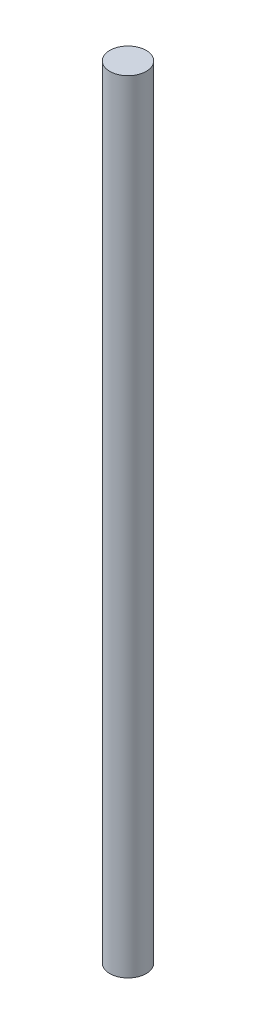
SolidWorks part; units mm, degrees
ref_plane "Płaszczyzna przednia" through (0, 0, 0) normal (0, 0, 1) x (1, 0, 0)
ref_plane "Płaszczyzna górna" through (0, 0, 0) normal (0, 1, 0) x (1, 0, 0)
ref_plane "Płaszczyzna prawa" through (0, 0, 0) normal (1, 0, 0) x (0, 0, -1)
sketch "Szkic5" plane through (0, 0, 0) normal (0, 1, 0) x (1, 0, 0)
  line L0 (0, 0) -> (2.4, 0) construction
  circle A0 centre (2.4, 0) radius 2.4
  dimension "D1" = 2.4
extrude "Dodanie-wyciągnięcie2" add sketch "Szkic5" along normal blind 103
sketch "Szkic6" plane through (0, 0, 0) normal (1, 0, 0) x (0, 0, -1)
  line L0 (0, 0) -> (0, 2.5) construction
  line L1 (0, 2.5) -> (0, 11.5) construction
  line L2 (0, 11.5) -> (0, 91.5) construction
  line L3 (0, 91.5) -> (0, 100.5) construction
  circle A0 centre (0, 2.5) radius 1.5
  circle A1 centre (0, 11.5) radius 1.5
  circle A2 centre (0, 91.5) radius 1.5
  circle A3 centre (0, 100.5) radius 1.5
  dimension "D3" = 3
  dimension "D4" = 3
  dimension "D6" = 3
  dimension "D7" = 3
  dimension "D1" = 2.5
  dimension "D2" = 9
  dimension "D5" = 80
  dimension "D8" = 9
extrude "Wytnij-wyciągnięcie1" cut sketch "Szkic6" along normal blind 3
